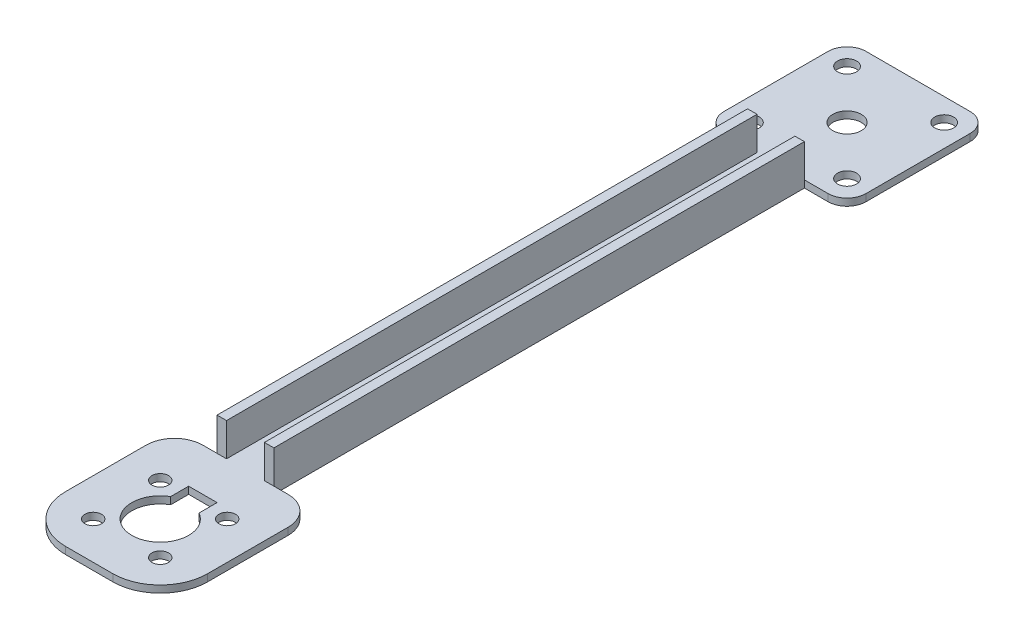
SolidWorks part; units mm, degrees
ref_plane "前视基准面" through (0, 0, 0) normal (0, 0, 1) x (1, 0, 0)
ref_plane "上视基准面" through (0, 0, 0) normal (0, 1, 0) x (1, 0, 0)
ref_plane "右视基准面" through (0, 0, 0) normal (1, 0, 0) x (0, 0, -1)
other "Configuration Table"
sketch "草图2" plane through (0, 0, 0) normal (0, 1, 0) x (1, 0, 0)
  line L0 (-15, 8) -> (15, 8)
  line L1 (-15, -23) -> (15, -23)
  line L5 (-15, -23) -> (15, 23) construction
  line L6 (-14.5817, 22.3586) -> (15, -23) construction
  line L7 (15, 8) -> (15, -23)
  line L8 (-15, 8) -> (-15, -23)
  circle A0 centre (0, 0) radius 3
extrude "凸台-拉伸1" add sketch "草图2" along normal blind 1.5
sketch "草图4" plane through (0, 1.5, 0) normal (0, 1, 0) x (1, 0, 0)
  line L1 (-15, -23) -> (15, -23)
  line L7 (-15, -160) -> (15, -160)
  line L9 (-15, -23) -> (-15, -160)
  line L10 (15, -23) -> (15, -160)
  circle A6 centre (7.0711, -137.9289) radius 1.75
  circle A8 centre (-7.0711, -152.0711) radius 1.75
  circle A9 centre (-7.0711, -137.9289) radius 1.75
  circle A10 centre (7.0711, -152.0711) radius 1.75
  circle A11 centre (0, -145) radius 6
  point P0 (0, -145)
  point P10 (0, -145)
extrude "凸台-拉伸2" add sketch "草图4" against normal blind 1.5
sketch "草图5" plane through (0, 1.5, 0) normal (0, 1, 0) x (1, 0, 0)
  line L1 (-3, -136) -> (3, -136)
  line L2 (-3, -136) -> (-3, -142)
  line L3 (-3, -142) -> (3, -142)
  line L4 (3, -136) -> (3, -142)
  line L5 (-3, -136) -> (3, -142) construction
  line L6 (-3, -142) -> (3, -136) construction
  circle A0 centre (0, -145) radius 6 construction
  point P0 (0, -139)
extrude "切除-拉伸1" cut sketch "草图5" against normal through all
fillet "圆角7" radius 10 2 edges at (15, 0.75, 160) (-15, 0.75, 160)
sketch "草图6" plane through (0, 1.5, 0) normal (0, 1, 0) x (1, 0, 0)
  line L0 (-8, 8) -> (-8, -8)
  line L1 (-15, 8) -> (-8, 8)
  line L2 (-15, 8) -> (-15, -127)
  line L3 (-15, -127) -> (-8, -127)
  line L5 (15, 8) -> (8, 8)
  line L6 (15, 8) -> (15, -127)
  line L7 (15, -127) -> (8, -127)
  line L9 (-8, -8) -> (-4, -8)
  line L10 (8, -8) -> (8, 8)
  line L11 (-4, -8) -> (-4, -127)
  line L12 (-4, -127) -> (-8, -127)
  line L13 (4, -8) -> (4, -127)
  line L14 (4, -127) -> (8, -127)
  line L15 (8, -8) -> (4, -8)
extrude "切除-拉伸2" cut sketch "草图6" against normal through all
fillet "圆角10" radius 6 2 edges at (15, 0.75, 127) (-15, 0.75, 127)
sketch "草图7" plane through (0, 1.5, 0) normal (0, 1, 0) x (1, 0, 0)
  line L5 (-10.253, -10.253) -> (10.253, 10.253) construction
  line L6 (-10.253, 10.253) -> (10.253, -10.253) construction
  line L7 (-15, -15) -> (15, -15)
  line L8 (-15, -15) -> (-15, 15)
  line L9 (-15, 15) -> (15, 15)
  line L10 (15, -15) -> (15, 15)
  line L11 (-15, -15) -> (15, 15) construction
  line L12 (-15, 15) -> (15, -15) construction
  circle A0 centre (0, 0) radius 3
  circle A3 centre (-10.253, 10.253) radius 2
  circle A4 centre (10.253, 10.253) radius 2
  circle A5 centre (-10.253, -10.253) radius 2
  circle A6 centre (10.253, -10.253) radius 2
extrude "凸台-拉伸3" add sketch "草图7" against normal blind 1.5
fillet "圆角12" radius 4 4 edges at (15, 0.75, 15) (15, 0.75, -15) (-15, 0.75, 15) (-15, 0.75, -15)
sketch "草图8" plane through (0, 1.5, 0) normal (0, 1, 0) x (1, 0, 0)
  line L0 (-4, -15) -> (-4, -127)
  line L1 (-4, -127) -> (-6, -127)
  line L2 (-9, -127) -> (-4, -127) construction
  line L3 (-6, -127) -> (-6, -15)
  line L4 (-11, -15) -> (-4, -15) construction
  line L5 (-6, -15) -> (-4, -15)
  line L6 (4, -15) -> (6, -15)
  line L7 (4, -15) -> (11, -15) construction
  line L8 (6, -15) -> (6, -127)
  line L9 (4, -127) -> (9, -127) construction
  line L10 (6, -127) -> (4, -127)
  line L11 (4, -127) -> (4, -15)
extrude "凸台-拉伸4" add sketch "草图8" along normal blind 7 and the other way blind 1.5
